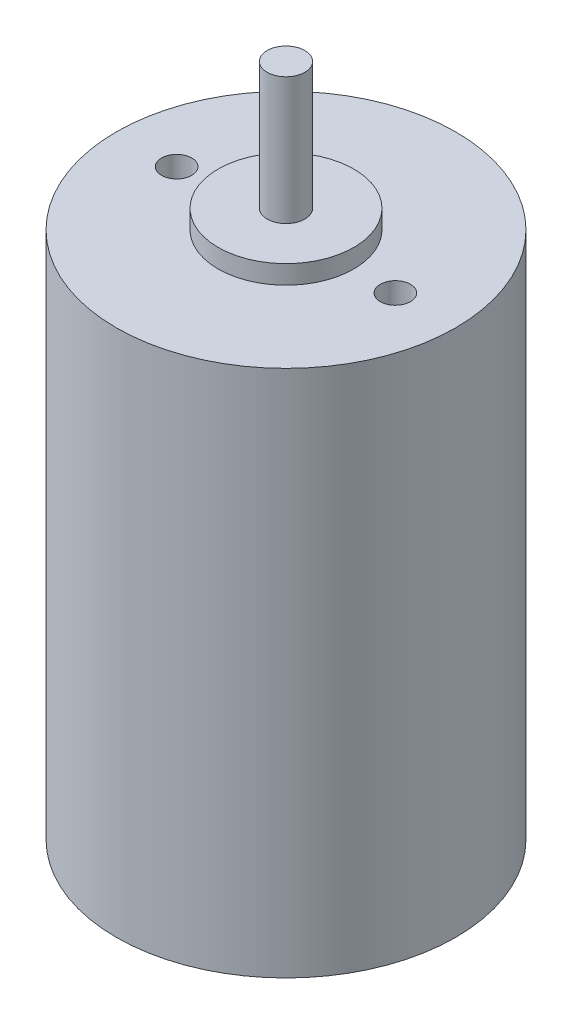
SolidWorks part; units mm, degrees
ref_plane "Front Plane" through (0, 0, 0) normal (0, 0, 1) x (1, 0, 0)
ref_plane "Top Plane" through (0, 0, 0) normal (0, 1, 0) x (1, 0, 0)
ref_plane "Right Plane" through (0, 0, 0) normal (1, 0, 0) x (0, 0, -1)
sketch "Sketch1" plane through (0, 0, 0) normal (0, 1, 0) x (1, 0, 0)
  circle A0 centre (0, 0) radius 22.5
  dimension "D1" = 45
extrude "Boss-Extrude1" add sketch "Sketch1" along normal blind 70
sketch "Sketch2" plane through (0, 70, 0) normal (0, 1, 0) x (1, 0, 0)
  circle A0 centre (0, 0) radius 9
  dimension "D1" = 18
extrude "Boss-Extrude2" add sketch "Sketch2" along normal blind 2.48
sketch "Sketch3" plane through (0, 72.48, 0) normal (0, 1, 0) x (1, 0, 0)
  circle A0 centre (0, 0) radius 2.5
  dimension "D1" = 5
extrude "Boss-Extrude3" add sketch "Sketch3" along normal blind 16.86
sketch "Sketch4" plane through (0, 70, 0) normal (0, 1, 0) x (1, 0, 0)
  circle A0 centre (-14.5, 0) radius 2
  circle A1 centre (14.5, 0) radius 2
  dimension "D1" = 4
  dimension "D3" = 4
  dimension "D2" = 14.5
  dimension "D4" = 14.5
extrude "Cut-Extrude1" cut sketch "Sketch4" against normal blind 4
